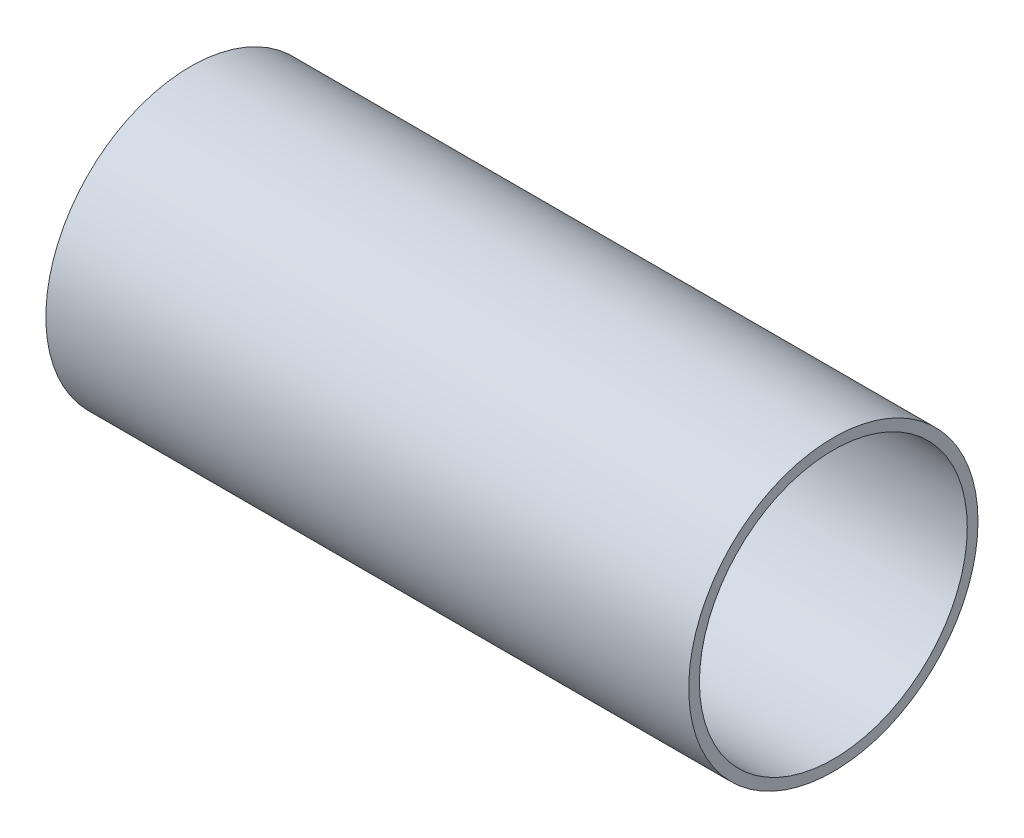
SolidWorks part; units mm, degrees
ref_plane "Front Plane" through (0, 0, 0) normal (0, 0, 1) x (1, 0, 0)
ref_plane "Top Plane" through (0, 0, 0) normal (0, 1, 0) x (1, 0, 0)
ref_plane "Right Plane" through (0, 0, 0) normal (1, 0, 0) x (0, 0, -1)
sketch "Sketch1" plane through (0, 0, 0) normal (1, 0, 0) x (0, 0, -1)
  circle A0 centre (0, 0) radius 34.29
  circle A2 centre (0, 0) radius 31.75
sketch3d "3DSketch1"
  line L0 (0, 0, 0) -> (-152.4, 0, 0)
sweep "Sweep1" add profiles "Sketch1" path "3DSketch1"
